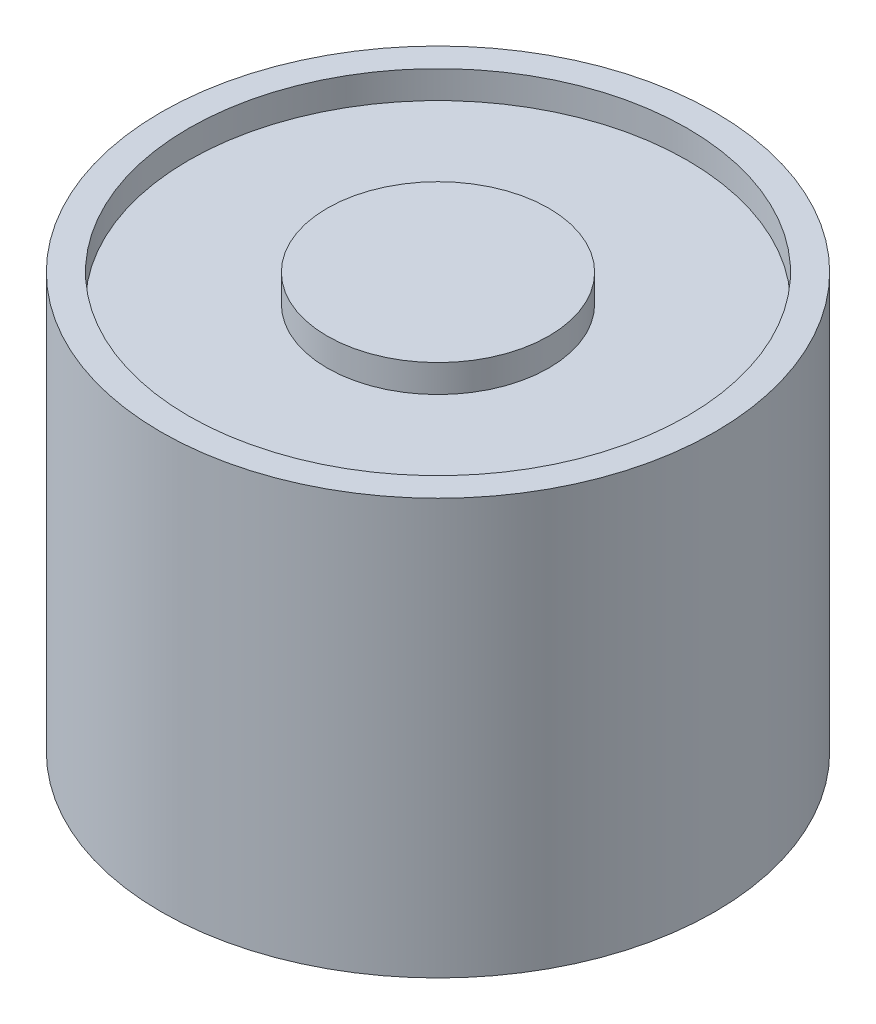
SolidWorks part; units mm, degrees
ref_plane "Front Plane" through (0, 0, 0) normal (0, 0, 1) x (1, 0, 0)
ref_plane "Top Plane" through (0, 0, 0) normal (0, 1, 0) x (1, 0, 0)
ref_plane "Right Plane" through (0, 0, 0) normal (1, 0, 0) x (0, 0, -1)
sketch "Sketch1" plane through (0, 0, 0) normal (0, 1, 0) x (1, 0, 0)
  circle A0 centre (0, 0) radius 10
  dimension "D1" = 20
extrude "Boss-Extrude1" add sketch "Sketch1" along normal blind 15
sketch "Sketch2" plane through (0, 15, 0) normal (0, 1, 0) x (1, 0, 0)
  circle A0 centre (0, 0) radius 9
  circle A1 centre (0, 0) radius 4
  dimension "D1" = 9
  dimension "D2" = 8
extrude "Cut-Extrude1" cut sketch "Sketch2" against normal blind 1
sketch "Sketch3" plane through (0, 0, 0) normal (0, -1, 0) x (1, 0, 0)
  circle A0 centre (0, 0) radius 1.7
  dimension "D1" = 3.4
extrude "Cut-Extrude2" cut sketch "Sketch3" against normal blind 4
